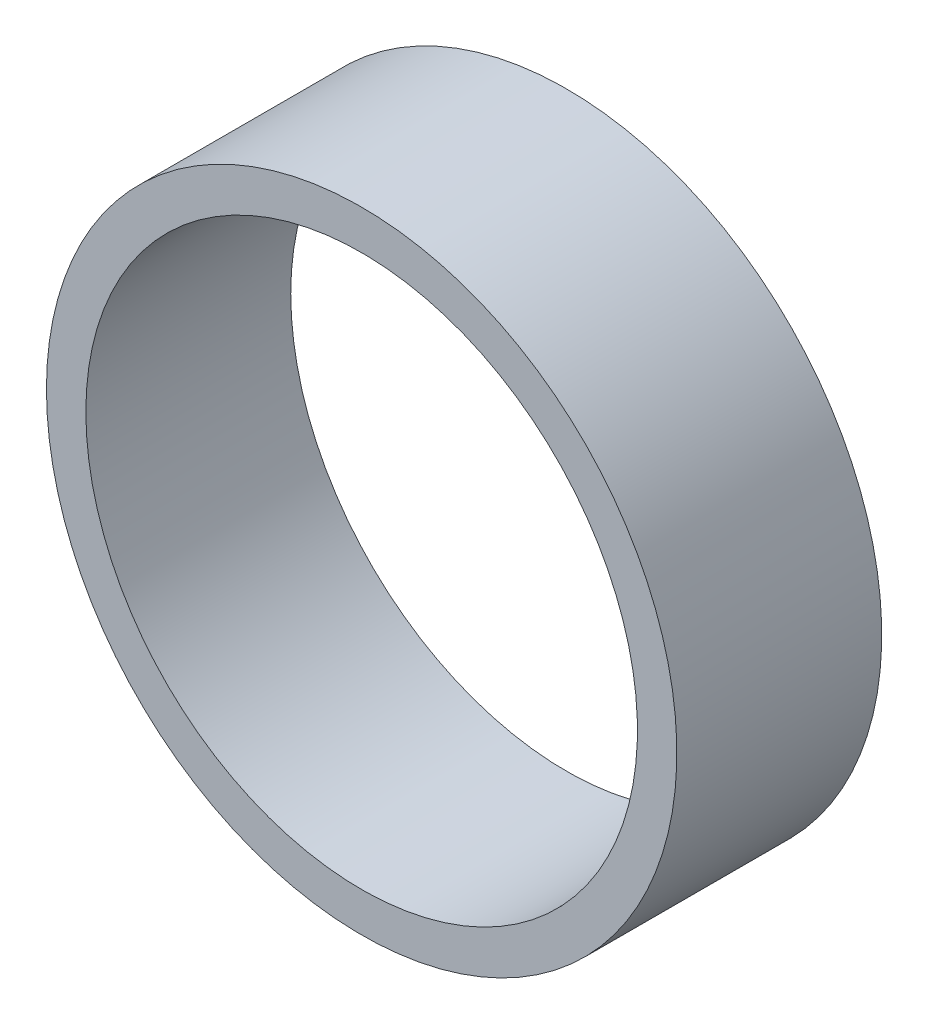
SolidWorks part; units mm, degrees
ref_plane "前视基准面" through (0, 0, 0) normal (0, 0, 1) x (1, 0, 0)
ref_plane "上视基准面" through (0, 0, 0) normal (0, 1, 0) x (1, 0, 0)
ref_plane "右视基准面" through (0, 0, 0) normal (1, 0, 0) x (0, 0, -1)
sketch "草图1" plane through (0, 0, 0) normal (0, 0, 1) x (1, 0, 0)
  circle A0 centre (0, 0) radius 17.5
  circle A1 centre (0, 0) radius 20
  dimension "D1" = 35
  dimension "D2" = 40
extrude "凸台-拉伸1" add sketch "草图1" along normal blind 13
